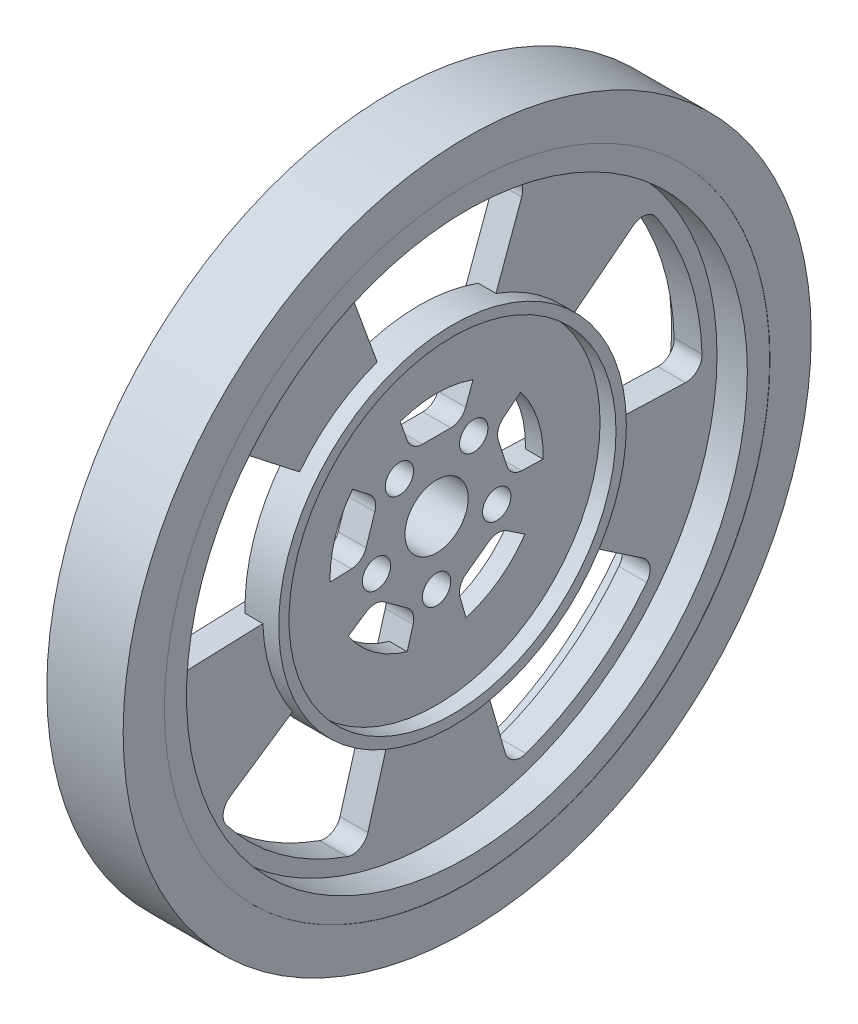
SolidWorks part; units mm, degrees
ref_plane "Front Plane" through (0, 0, 0) normal (0, 0, 1) x (1, 0, 0)
ref_plane "Top Plane" through (0, 0, 0) normal (0, 1, 0) x (1, 0, 0)
ref_plane "Right Plane" through (0, 0, 0) normal (1, 0, 0) x (0, 0, -1)
sketch "Sketch1" plane through (0, 0, 0) normal (1, 0, 0) x (0, 0, -1)
  circle A0 centre (0, 0) radius 34.544
  dimension "D1" = 69.088
extrude "Boss-Extrude1" add sketch "Sketch1" along normal blind 7.62
sketch "Sketch2" plane through (7.62, 0, 0) normal (1, 0, 0) x (0, 0, -1)
  circle A0 centre (0, 0) radius 28.1686
  dimension "D1" = 56.3372
extrude "Cut-Extrude1" cut sketch "Sketch2" against normal blind 3.048
sketch "Sketch3" plane through (0, 0, 0) normal (-1, 0, 0) x (0, 0, 1)
  circle A0 centre (0, 0) radius 28.1686
  circle A1 centre (0, 0) radius 4.3688
  dimension "D1" = 56.3372
  dimension "D2" = 8.7376
extrude "Cut-Extrude2" cut sketch "Sketch3" against normal blind 1.778
sketch "Sketch4" plane through (1.778, 0, 0) normal (-1, 0, 0) x (0, 0, 1)
  line L0 (0, 0) -> (0, 34.544) construction
  line L1 (-2.54, 6.985) -> (2.54, 6.985)
  line L2 (2.54, 6.985) -> (9.1143, 25.0643)
  line L3 (-9.1143, 25.0643) -> (-2.54, 6.985)
  circle A0 centre (0, 0) radius 34.544 construction
  arc A1 (9.1143, 25.0643) -> (-9.1143, 25.0643) centre (0, 0) ccw
  circle A2 centre (0, 0) radius 28.1686 construction
  dimension "D3" = 26.67
  dimension "D1" = 5.08
  dimension "D2" = 6.985
extrude "Cut-Extrude3" cut sketch "Sketch4" against normal through all
fillet "Fillet1" radius 1.6002 4 edges at (3.175, 25.0643, 9.1143) (3.175, 25.0643, -9.1143) (3.175, 6.985, 2.54) (3.175, 6.985, -2.54)
pattern_circular "CirPattern1" count 5 over 360 about axis through (0, 0, 0) along (1, 0, 0) of "Fillet1", "Cut-Extrude3"
sketch "Sketch5" plane through (4.572, 0, 0) normal (1, 0, 0) x (0, 0, -1)
  circle A0 centre (0, 0) radius 17.4625
  circle A1 centre (0, 0) radius 10.7061
  dimension "D1" = 34.925
  dimension "D2" = 21.4122
extrude "Boss-Extrude2" add sketch "Sketch5" against normal blind 1.778
sketch "Sketch6" plane through (4.572, 0, 0) normal (1, 0, 0) x (0, 0, -1)
  circle A0 centre (0, 0) radius 17.4625
  circle A1 centre (0, 0) radius 16.4211
  dimension "D1" = 34.925
  dimension "D2" = 1.0414
extrude "Boss-Extrude4" add sketch "Sketch6" along normal blind 1.6002
sketch "Sketch7" plane through (4.572, 0, 0) normal (1, 0, 0) x (0, 0, -1)
  circle A0 centre (0, 0) radius 3.175
  dimension "D1" = 6.35
extrude "Cut-Extrude4" cut sketch "Sketch7" against normal through all
sketch "Sketch8" plane through (4.572, 0, 0) normal (1, 0, 0) x (0, 0, -1)
  circle A0 centre (0, -6.35) radius 1.4224
  dimension "D1" = 2.8448
  dimension "D2" = 6.35
extrude "Cut-Extrude5" cut sketch "Sketch8" against normal through all
pattern_circular "CirPattern2" count 5 over 360 about axis through (0, 0, 0) along (1, 0, 0) of "Cut-Extrude5"
sketch "Sketch9" plane through (7.62, 0, 0) normal (1, 0, 0) x (0, 0, -1)
  circle A0 centre (0, 0) radius 34.5567
  circle A1 centre (0, 0) radius 30.4165
  dimension "D1" = 69.1134
  dimension "D2" = 60.833
extrude "Boss-Extrude5" add sketch "Sketch9" along normal blind 0.0254 and the other way blind 7.6454
scale "缩放比例1" scale about origin uniform scaling yes scale factor 3
